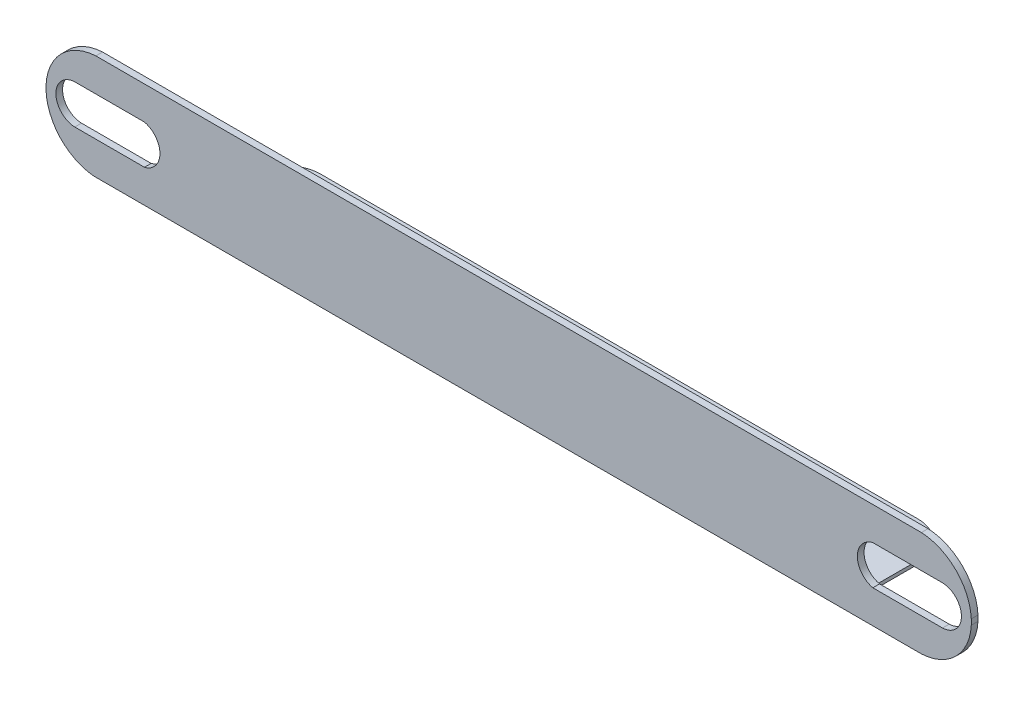
SolidWorks part; units mm, degrees
ref_plane "Front Plane" through (0, 0, 0) normal (0, 0, 1) x (1, 0, 0)
ref_plane "Top Plane" through (0, 0, 0) normal (0, 1, 0) x (1, 0, 0)
ref_plane "Right Plane" through (0, 0, 0) normal (1, 0, 0) x (0, 0, -1)
sketch "Sketch1" plane through (0, 0, 0) normal (0, 0, 1) x (1, 0, 0)
  line L1 (-175.514, 19.939) -> (175.514, 19.939)
  line L2 (-175.514, 19.939) -> (-175.514, -19.939)
  line L3 (-175.514, -19.939) -> (175.514, -19.939)
  line L4 (175.514, 19.939) -> (175.514, -19.939)
  dimension "D1" = 39.878
  dimension "D2" = 351.028
  dimension "D3" = 175.514
  dimension "D4" = 19.939
extrude "Boss-Extrude1" add sketch "Sketch1" along normal blind 2.54 contours L3 L4 L1 L2
sketch "Sketch2" plane through (0, 0, 2.54) normal (0, 0, 1) x (1, 0, 0)
  line L0 (-156.6104, 19.939) -> (-175.514, 19.939)
  line L1 (-175.514, 19.939) -> (-175.514, -19.939)
  line L2 (-175.514, -19.939) -> (-157.4875, -19.939)
  line L3 (156.5895, 19.939) -> (175.514, 19.939)
  line L4 (175.514, 19.939) -> (175.514, -19.939)
  line L5 (175.514, -19.939) -> (156.5895, -19.939)
  arc A0 (-157.4875, -19.939) -> (-156.6104, 19.939) centre (-155.5205, -0.0336) cw
  arc A1 (156.5895, -19.939) -> (156.5895, 19.939) centre (155.5768, 0) ccw
  line M1 (-175.514, 19.939) -> (-175.514, -19.939)
  line M2 (-175.514, -19.939) -> (175.514, -19.939)
  line M3 (175.514, -19.939) -> (175.514, 19.939)
  line M4 (175.514, 19.939) -> (-175.514, 19.939)
extrude "Cut-Extrude1" cut sketch "Sketch2" against normal blind 2.54 contours A0 M1 M4 | A0 M2 M1 | A1 M3 M4 | A1 M2 M3
ref_plane "Plane1" through (0, -19.939, 0) normal (0, -1, 0) x (-1, 0, 0)
sketch "Sketch4" plane through (0, -19.939, 0) normal (0, -1, 0) x (-1, 0, 0)
  line L6 (-126.4905, 27.1297) -> (-126.4905, 0)
  line L8 (-126.4905, 0) -> (127.3885, 0)
  line L11 (127.3885, 0) -> (127.3885, 26.2316)
  line L13 (113.7546, 39.878) -> (-112.6159, 39.878)
  arc A0 (-112.6159, 39.878) -> (-126.4905, 27.1297) centre (-112.8713, 26.2316) ccw
  arc A1 (127.3885, 26.2316) -> (113.7546, 39.878) centre (113.7398, 26.2293) ccw
extrude "Boss-Extrude3" add sketch "Sketch4" against normal blind 1.27
sketch "Sketch5" plane through (0, 0, 0) normal (0, 0, -1) x (-1, 0, 0)
  line L0 (-164.6061, 7.4157) -> (-164.6061, -7.4214) construction
  line L1 (0, 0) -> (-175.514, 0) construction
  line L2 (-164.6061, 7.4157) -> (-138.1642, 7.4157)
  line L3 (-164.6061, -7.4214) -> (-138.1642, -7.4214)
  arc A0 (-164.6061, -7.4214) -> (-164.6061, 7.4157) centre (-164.3507, -0.0029) cw
  arc A1 (-138.1642, 7.4157) -> (-138.1642, -7.4214) centre (-139.9047, -0.0029) cw
extrude "Cut-Extrude2" cut sketch "Sketch5" against normal through all
ref_plane "Plane2" through (0, 0, 0) normal (1, 0, 0) x (0, 0, -1)
mirror "Mirror1" about plane through (0, 0, 0) normal (1, 0, 0) of "Cut-Extrude2"
